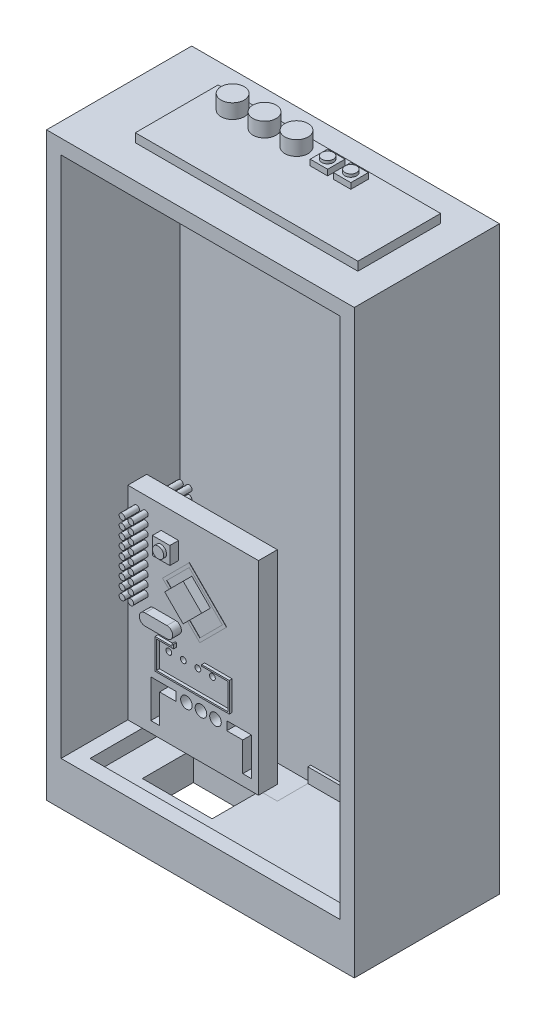
SolidWorks part; units mm, degrees
ref_plane "前基準面" through (0, 0, 0) normal (0, 0, 1) x (1, 0, 0)
ref_plane "上基準面" through (0, 0, 0) normal (0, 1, 0) x (1, 0, 0)
ref_plane "右基準面" through (0, 0, 0) normal (1, 0, 0) x (0, 0, -1)
sketch "草圖1" plane through (0, 0, 0) normal (0, 1, 0) x (1, 0, 0)
  line L1 (-53, 22.5) -> (53, 22.5)
  line L2 (-53, 22.5) -> (-53, -22.5)
  line L3 (-53, -22.5) -> (53, -22.5)
  line L4 (53, 22.5) -> (53, -22.5)
  line L5 (-53, 22.5) -> (53, -22.5) construction
  line L6 (-53, -22.5) -> (53, 22.5) construction
  point P0 (0, 0)
  dimension "D1" = 106
  dimension "D2" = 45
extrude "填料-伸長1" add sketch "草圖1" along normal blind 200
sketch "草圖2" plane through (0, 0, 22.5) normal (0, 0, 1) x (1, 0, 0)
  line L0 (-53, 200) -> (-53, 0) construction
  line L1 (-43, 190) -> (43, 190)
  line L2 (-43, 190) -> (-43, 10)
  line L3 (-43, 10) -> (43, 10)
  line L4 (43, 190) -> (43, 10)
  line L5 (-53, 200) -> (53, 200) construction
  line L6 (53, 200) -> (53, 0) construction
  line L7 (-53, 0) -> (53, 0) construction
  dimension "D1" = 10
  dimension "D2" = 10
  dimension "D3" = 10
  dimension "D4" = 10
extrude "除料-伸長1" cut sketch "草圖2" against normal blind 35
sketch "草圖4" plane through (0, 0, 0) normal (0, -1, 0) x (1, 0, 0)
  line L0 (-53, -22.5) -> (-53, 22.5) construction
  line L1 (-33, 14.5) -> (-8.9694, 14.5)
  line L2 (-33, 14.5) -> (-33, 7.292)
  line L3 (-33, 7.292) -> (-8.9694, 7.292)
  line L4 (-8.9694, 14.5) -> (-8.9694, 7.292)
  line L5 (-53, 22.5) -> (53, 22.5) construction
  dimension "D1" = 20
  dimension "D2" = 8
extrude "除料-伸長4" cut sketch "草圖4" against normal blind 35
sketch "草圖5" plane through (0, 0, 22.5) normal (0, 0, 1) x (1, 0, 0)
  line L1 (-53, 200) -> (53, 200)
  line L2 (-53, 200) -> (-53, 0)
  line L3 (-53, 0) -> (53, 0)
  line L4 (53, 200) -> (53, 0)
extrude "填料-伸長2" add sketch "草圖5" along normal blind 5
sketch "草圖6" plane through (0, 0, 27.5) normal (0, 0, 1) x (1, 0, 0)
  line L0 (-53, 200) -> (-53, 0) construction
  line L1 (-48, 195) -> (48, 195)
  line L2 (-48, 195) -> (-48, 15)
  line L3 (-48, 15) -> (48, 15)
  line L4 (48, 195) -> (48, 15)
  line L5 (53, 200) -> (-53, 200) construction
  line L6 (53, 0) -> (53, 200) construction
  line L7 (-53, 0) -> (53, 0) construction
  dimension "D1" = 5
  dimension "D2" = 5
  dimension "D3" = 5
  dimension "D4" = 15
extrude "除料-伸長5" cut sketch "草圖6" against normal blind 41
sketch "草圖7" plane through (0, 0, -13.5) normal (0, 0, 1) x (1, 0, 0)
  line L0 (-48, 195) -> (-48, 15) construction
  line L1 (-48, 85) -> (-3, 85)
  line L2 (-48, 85) -> (-48, 15)
  line L3 (-48, 15) -> (-3, 15)
  line L4 (-3, 85) -> (-3, 15)
  line L5 (-48, 15) -> (48, 15) construction
  dimension "D1" = 70
  dimension "D2" = 45
extrude "填料-伸長3" add sketch "草圖7" along normal blind 18
sketch "草圖8" plane through (0, 0, 0) normal (0, -1, 0) x (1, 0, 0)
  line L1 (-33, 14.5) -> (-8.9694, 14.5)
  line L2 (-33, 14.5) -> (-33, -3.0598)
  line L3 (-33, -3.0598) -> (-8.9694, -3.0598)
  line L4 (-8.9694, 14.5) -> (-8.9694, -3.0598)
extrude "除料-伸長6" cut sketch "草圖8" against normal blind 15
sketch "草圖9" plane through (0, 0, -13.5) normal (0, 0, 1) x (1, 0, 0)
  line L0 (-34, -815) -> (-34, 49185) construction
  line L2 (34, -815) -> (34, 49185) construction
  line L4 (-48, 195) -> (-48, 15) construction
  line L5 (48, 15) -> (48, 195) construction
  line L6 (-1038, 185) -> (48962, 185) construction
  line L7 (-1038, 175) -> (48962, 175) construction
  line L9 (48, 195) -> (-48, 195) construction
  line L10 (48, 195) -> (-48, 195) construction
  circle A0 centre (-34, 185) radius 3.5
  circle A1 centre (-34, 175) radius 3.5
  circle A2 centre (34, 185) radius 3.5
  circle A3 centre (34, 175) radius 3.5
  dimension "D5" = 7
  dimension "D6" = 7
  dimension "D7" = 7
  dimension "D8" = 7
  dimension "D1" = 14
  dimension "D2" = 14
  dimension "D3" = 10
  dimension "D4" = 20
extrude "除料-伸長7" cut sketch "草圖9" against normal through all
sketch "草圖11" plane through (0, 0, 4.5) normal (0, 0, 1) x (1, 0, 0)
  line L1 (-36.5315, 77.2499) -> (-30.5315, 77.2499)
  line L2 (-36.5315, 77.2499) -> (-36.5315, 71.2499)
  line L3 (-36.5315, 71.2499) -> (-30.5315, 71.2499)
  line L4 (-30.5315, 77.2499) -> (-30.5315, 71.2499)
  circle A0 centre (-33.5925, 74.1521) radius 1.9254
  dimension "D1" = 6
  dimension "D2" = 6
extrude "填料-伸長5" add sketch "草圖11" along normal blind 3
sketch "草圖12" plane through (0, 0, 7.5) normal (0, 0, 1) x (1, 0, 0)
  circle A0 centre (-33.5925, 74.1521) radius 1.9254
extrude "填料-伸長6" add sketch "草圖12" along normal blind 1 separate body
sketch "草圖14" plane through (0, 0, 4.5) normal (0, 0, 1) x (1, 0, 0)
  line L1 (-32.3103, 62.5201) -> (-25.9463, 68.884)
  line L2 (-32.3103, 62.5201) -> (-25.9463, 56.1561)
  line L3 (-25.9463, 56.1561) -> (-19.5824, 62.5201)
  line L4 (-25.9463, 68.884) -> (-19.5824, 62.5201)
  dimension "D1" = 9
  dimension "D2" = 9
extrude "填料-伸長7" add sketch "草圖14" along normal blind 3
sketch "草圖22" plane through (0, 0, 4.5) normal (0, 0, 1) x (1, 0, 0)
  line L0 (-39.0776, 50.8915) -> (-31.5286, 50.8915) construction
  line L1 (-39.0776, 52.8686) -> (-31.5286, 52.8686)
  line L2 (-39.0776, 48.9143) -> (-31.5286, 48.9143)
  arc A0 (-39.0776, 52.8686) -> (-39.0776, 48.9143) centre (-39.0776, 50.8915) ccw
  arc A1 (-31.5286, 48.9143) -> (-31.5286, 52.8686) centre (-31.5286, 50.8915) ccw
  point P2 (-35.3031, 50.8915)
extrude "填料-伸長12" add sketch "草圖22" along normal blind 3
sketch "草圖23" plane through (0, 0, 4.5) normal (0, 0, 1) x (1, 0, 0)
  line L0 (-40.0744, 18.7432) -> (-37.0744, 18.7432)
  line L1 (-37.0744, 18.7432) -> (-37.0744, 28.7885)
  line L2 (-37.0744, 28.7885) -> (-31.4645, 28.7885)
  line L3 (-31.4645, 28.7885) -> (-31.4645, 31.7885)
  line L4 (-31.4645, 31.7885) -> (-40.0744, 31.7885)
  line L5 (-40.0744, 31.7885) -> (-40.0744, 18.7432)
  line L6 (-1031.4645, 30.2885) -> (48968.5355, 30.2885) construction
  line L7 (-1037.0744, 28.7885) -> (48962.9256, 28.7885) construction
  line L8 (-1037.0744, 18.7432) -> (48962.9256, 18.7432) construction
  line L9 (-8.4235, 18.7432) -> (-5.4235, 18.7432)
  line L10 (-5.4235, 18.7432) -> (-5.4235, 31.7885)
  line L11 (-5.4235, 31.7885) -> (-13.9289, 31.7885)
  line L12 (-13.9289, 31.7885) -> (-13.9289, 28.7885)
  line L13 (-13.9289, 28.7885) -> (-8.4235, 28.7885)
  line L14 (-8.4235, 28.7885) -> (-8.4235, 18.7432)
  circle A0 centre (-27.8147, 30.2885) radius 2
  circle A1 centre (-22.8147, 30.2885) radius 2
  circle A2 centre (-17.8147, 30.2885) radius 2
  point P9 (-31.4645, 30.2885)
  dimension "D3" = 4
  dimension "D4" = 4
  dimension "D5" = 5
  dimension "D6" = 5
  dimension "D7" = 4
  dimension "D1" = 3
  dimension "D2" = 3
  dimension "D8" = 8.6099
  dimension "D9" = 3
  dimension "D10" = 3
  dimension "D11" = 3
  dimension "D12" = 3
extrude "除料-伸長8" cut sketch "草圖23" against normal blind 12
sketch "草圖24" plane through (0, 0, 4.5) normal (0, 0, 1) x (1, 0, 0)
  line L0 (-26.7611, 71.1131) -> (-34.5393, 63.3349)
  line L1 (-34.5393, 63.3349) -> (-23.1179, 51.9135)
  line L2 (-23.1179, 51.9135) -> (-15.3397, 59.6916)
  line L3 (-15.3397, 59.6916) -> (-26.7611, 71.1131)
  line L4 (-19.5824, 62.5201) -> (-25.9463, 68.884) construction
  line L5 (-32.3103, 62.5201) -> (-25.9463, 56.1561) construction
  line L6 (-25.9463, 56.1561) -> (-19.5824, 62.5201) construction
  point P10 (-22.7643, 59.3381)
  dimension "D1" = 1
  dimension "D2" = 1
  dimension "D3" = 5
extrude "伸長-薄件1" add sketch "草圖24" along normal blind 0.1 thin
sketch "草圖25" plane through (0, 85, 0) normal (0, 1, 0) x (1, 0, 0)
  line L0 (-48, -4.5) -> (-48, 13.5) construction
  line L1 (-3, 13.5) -> (-48, 13.5)
  line L2 (-3, 13.5) -> (-3, 8.5)
  line L3 (-3, 8.5) -> (-48, 8.5)
  line L4 (-48, 13.5) -> (-48, 8.5)
  dimension "D1" = 5
extrude "除料-伸長9" cut sketch "草圖25" against normal blind 75.1
sketch "草圖26" plane through (0, 85, 0) normal (0, 1, 0) x (1, 0, 0)
  line L0 (-48, -4.5) -> (-48, 8.5) construction
  line L1 (-3, 8.5) -> (-48, 8.5)
  line L2 (-3, 8.5) -> (-3, 2)
  line L3 (-3, 2) -> (-48, 2)
  line L4 (-48, 8.5) -> (-48, 2)
extrude "除料-伸長10" cut sketch "草圖26" against normal blind 75.1
sketch "草圖10" plane through (0, 0, 4.5) normal (0, 0, 1) x (1, 0, 0)
  line L0 (-45, -915) -> (-45, 49085) construction
  line L2 (-6, -915) -> (-6, 49085) construction
  line L4 (-48, 195) -> (-48, 15) construction
  line L5 (-3, 15) -> (-3, 85) construction
  line L6 (-42, -915) -> (-42, 49085) construction
  line L8 (-9, -915) -> (-9, 49085) construction
  circle A0 centre (-45, 79.5958) radius 1
  circle A1 centre (-42, 79.5958) radius 1
  circle A2 centre (-45, 76.5958) radius 1
  circle A3 centre (-42, 76.5958) radius 1
  circle A4 centre (-45, 73.5958) radius 1
  circle A5 centre (-42, 73.5958) radius 1
  circle A6 centre (-45, 70.5958) radius 1
  circle A7 centre (-42, 70.5958) radius 1
  circle A8 centre (-45, 67.5958) radius 1
  circle A9 centre (-42, 67.5958) radius 1
  circle A10 centre (-45, 64.5958) radius 1
  circle A11 centre (-42, 64.5958) radius 1
  circle A12 centre (-45, 61.5958) radius 1
  circle A13 centre (-42, 61.5958) radius 1
  circle A14 centre (-45, 58.5958) radius 1
  circle A15 centre (-42, 58.5958) radius 1
  circle A16 centre (-45, 55.5958) radius 1
  circle A17 centre (-42, 55.5958) radius 1
  dimension "D5" = 2
  dimension "D6" = 2
  dimension "D7" = 2
  dimension "D8" = 2
  dimension "D9" = 2
  dimension "D10" = 2
  dimension "D11" = 2
  dimension "D12" = 2
  dimension "D13" = 2
  dimension "D14" = 2
  dimension "D15" = 2
  dimension "D16" = 2
  dimension "D17" = 3
  dimension "D18" = 3
  dimension "D19" = 3
  dimension "D20" = 3
  dimension "D21" = 3
  dimension "D22" = 3
  dimension "D23" = 3
  dimension "D24" = 3
  dimension "D25" = 3
  dimension "D26" = 3
  dimension "D27" = 2
  dimension "D28" = 2
  dimension "D29" = 2
  dimension "D30" = 2
  dimension "D31" = 2
  dimension "D32" = 2
  dimension "D33" = 3
  dimension "D34" = 3
  dimension "D35" = 3
  dimension "D36" = 3
  dimension "D37" = 3
  dimension "D38" = 3
  dimension "D1" = 3
  dimension "D2" = 3
  dimension "D3" = 3
  dimension "D4" = 3
extrude "填料-伸長4" add sketch "草圖10" along normal blind 5 and the other way blind 15.1
sketch "草圖27" plane through (0, 0, 4.5) normal (0, 0, 1) x (1, 0, 0)
  line L0 (-31.2039, 46.4183) -> (-31.2039, 45.0646)
  line L1 (-31.2039, 45.0646) -> (-37.1353, 45.0646)
  line L2 (-37.1353, 45.0646) -> (-37.1353, 35.6847)
  line L3 (-37.1353, 35.6847) -> (-12.5618, 35.6847)
  line L4 (-12.5618, 35.6847) -> (-12.5618, 44.7108)
  line L5 (-12.5618, 44.7108) -> (-21.5487, 44.7108)
  line L6 (-21.5487, 44.7108) -> (-21.5487, 45.2108)
  line L7 (-21.5487, 45.2108) -> (-12.0618, 45.2108)
  line L8 (-12.0618, 45.2108) -> (-12.0618, 35.1847)
  line L9 (-12.0618, 35.1847) -> (-37.6353, 35.1847)
  line L10 (-37.6353, 35.1847) -> (-37.6353, 45.5646)
  line L11 (-37.6353, 45.5646) -> (-31.7039, 45.5646)
  line L12 (-31.7039, 45.5646) -> (-31.7039, 46.4183)
  line L13 (-31.7039, 46.4183) -> (-31.2039, 46.4183)
  dimension "D1" = 0.5
  dimension "D2" = 0.5
  dimension "D3" = 0.5
  dimension "D4" = 0.5
  dimension "D5" = 0.5
  dimension "D6" = 0.5
extrude "填料-伸長14" add sketch "草圖27" along normal blind 1
sketch "草圖28" plane through (0, 0, 4.5) normal (0, 0, 1) x (1, 0, 0)
  line L0 (-1037.1353, 42.4079) -> (48962.8647, 42.4079) construction
  circle A0 centre (-33.8755, 42.4079) radius 1
  circle A1 centre (-28.8755, 42.4079) radius 1
  circle A2 centre (-23.8755, 42.4079) radius 1
  circle A3 centre (-18.8755, 42.4079) radius 1
  dimension "D1" = 2
  dimension "D2" = 2
  dimension "D3" = 2
  dimension "D4" = 2
  dimension "D5" = 5
  dimension "D6" = 5
  dimension "D7" = 5
extrude "除料-伸長11" cut sketch "草圖28" against normal blind 12.1
sketch "草圖30" plane through (0, 200, 0) normal (0, 1, 0) x (1, 0, 0)
  line L1 (-33.8385, 12.429) -> (42.8043, 12.429)
  line L2 (-33.8385, 12.429) -> (-33.8385, -16.0707)
  line L3 (-33.8385, -16.0707) -> (42.8043, -16.0707)
  line L4 (42.8043, 12.429) -> (42.8043, -16.0707)
extrude "填料-伸長15" add sketch "草圖30" along normal blind 3
sketch "草圖32" plane through (0, 203, 0) normal (0, 1, 0) x (1, 0, 0)
  line L0 (42.8043, 12.429) -> (-33.8385, 12.429) construction
  line L1 (-33.8385, 12.429) -> (-33.8385, -16.0707) construction
  circle A0 centre (-23.8385, 7.429) radius 4
  dimension "D1" = 5
  dimension "D2" = 8
  dimension "D3" = 10
extrude "填料-伸長17" add sketch "草圖32" along normal blind 5
sketch "草圖35" plane through (0, 203, 0) normal (0, 1, 0) x (1, 0, 0)
  line L0 (42.8043, 12.429) -> (-33.8385, 12.429) construction
  circle A0 centre (-12.8385, 7.429) radius 4
  circle A1 centre (-23.8385, 7.429) radius 4 construction
  dimension "D1" = 5
  dimension "D2" = 8
  dimension "D3" = 11
extrude "填料-伸長18" add sketch "草圖35" along normal blind 5
sketch "草圖36" plane through (0, 203, 0) normal (0, 1, 0) x (1, 0, 0)
  line L0 (42.8043, 12.429) -> (-33.8385, 12.429) construction
  circle A0 centre (-1.8385, 7.429) radius 4
  circle A1 centre (-12.8385, 7.429) radius 4 construction
  dimension "D1" = 5
  dimension "D2" = 8
  dimension "D3" = 11
extrude "填料-伸長19" add sketch "草圖36" along normal blind 5
sketch "草圖37" plane through (0, 203, 0) normal (0, 1, 0) x (1, 0, 0)
  line L0 (-1008.8178, 7.429) -> (48991.1822, 7.429) construction
  line L2 (6.1615, 10.1473) -> (12.1615, 10.1473)
  line L3 (6.1615, 10.1473) -> (6.1615, 4.1473)
  line L4 (6.1615, 4.1473) -> (12.1615, 4.1473)
  line L5 (12.1615, 10.1473) -> (12.1615, 4.1473)
  line L6 (14.1615, 10.1473) -> (20.1615, 10.1473)
  line L7 (14.1615, 10.1473) -> (14.1615, 4.1473)
  line L8 (14.1615, 4.1473) -> (20.1615, 4.1473)
  line L9 (20.1615, 10.1473) -> (20.1615, 4.1473)
  circle A0 centre (-1.8385, 7.429) radius 4 construction
  dimension "D1" = 6
  dimension "D2" = 6
  dimension "D3" = 6
  dimension "D4" = 8
  dimension "D5" = 2
extrude "填料-伸長20" add sketch "草圖37" along normal blind 2
sketch "草圖38" plane through (0, 205, 0) normal (0, 1, 0) x (1, 0, 0)
  line L0 (14.1615, 10.1473) -> (14.1615, 4.1473) construction
  line L1 (6.1615, 10.1473) -> (6.1615, 4.1473) construction
  line L2 (12.1615, 10.1473) -> (6.1615, 10.1473) construction
  line L3 (20.1615, 10.1473) -> (14.1615, 10.1473) construction
  circle A0 centre (9.1615, 7.1473) radius 2
  circle A1 centre (17.1615, 7.1473) radius 2
  dimension "D1" = 4
  dimension "D2" = 4
  dimension "D3" = 3
  dimension "D4" = 3
  dimension "D5" = 3
  dimension "D6" = 3
extrude "填料-伸長21" add sketch "草圖38" along normal blind 1
sketch "草圖39" plane through (0, 10, 0) normal (0, 1, 0) x (1, 0, 0)
  line L0 (43, -22.5) -> (43, 12.5) construction
  line L1 (-3, 12.5) -> (43, 12.5) construction
  circle A0 centre (36, 5.5) radius 6
  dimension "D1" = 12
  dimension "D2" = 7
  dimension "D3" = 7
extrude "填料-伸長22" add sketch "草圖39" along normal blind 60
sketch "草圖40" plane through (0, 70, 0) normal (0, 1, 0) x (1, 0, 0)
  line L1 (32.4604, 3.9294) -> (39.8369, 3.9294)
  line L2 (32.4604, 3.9294) -> (32.4604, 2.0018)
  line L3 (32.4604, 2.0018) -> (39.8369, 2.0018)
  line L4 (39.8369, 3.9294) -> (39.8369, 2.0018)
extrude "除料-伸長12" cut sketch "草圖40" against normal blind 23
sketch "草圖41" plane through (0, 70, 0) normal (0, 1, 0) x (1, 0, 0)
  line L1 (33.7325, 8.9297) -> (37.9957, 8.9297)
  line L2 (33.7325, 8.9297) -> (33.7325, 7.4469)
  line L3 (33.7325, 7.4469) -> (37.9957, 7.4469)
  line L4 (37.9957, 8.9297) -> (37.9957, 7.4469)
extrude "除料-伸長13" cut sketch "草圖41" against normal blind 23
sketch "草圖42" plane through (0, 0, 0) normal (0, 1, 0) x (1, 0, 0)
  line L0 (-59.7493, -30.1122) -> (-55.7853, -34.0763)
  line L1 (-55.7853, -34.0763) -> (-109.1584, -87.4494)
  line L2 (-109.1584, -87.4494) -> (-113.1224, -83.4853)
  line L3 (-113.1224, -83.4853) -> (-59.7493, -30.1122)
extrude "填料-伸長23" add sketch "草圖42" along normal blind 200 separate body
sketch "草圖43" plane through (0, 200, 0) normal (0, 1, 0) x (1, 0, 0)
  circle A0 centre (-56.349, -28.8579) radius 5.3338
extrude "填料-伸長24" add sketch "草圖43" against normal blind 200
sketch "草圖45" plane through (0, 200, 0) normal (0, 1, 0) x (1, 0, 0)
  line L0 (-51.1909, -27.5) -> (-45.6225, -33.0684)
  line L1 (-45.6225, -33.0684) -> (-108.6096, -96.0556)
  line L2 (-108.6096, -96.0556) -> (-126.7933, -77.872)
  line L3 (-126.7933, -77.872) -> (-59.1056, -19.5853)
  line L4 (-59.1056, -19.5853) -> (-53, -24.7065)
  line L5 (-53, -24.7065) -> (-53, -27.5)
  line L6 (-53, -27.5) -> (-51.1909, -27.5)
extrude "除料-伸長14" cut sketch "草圖45" against normal blind 207
